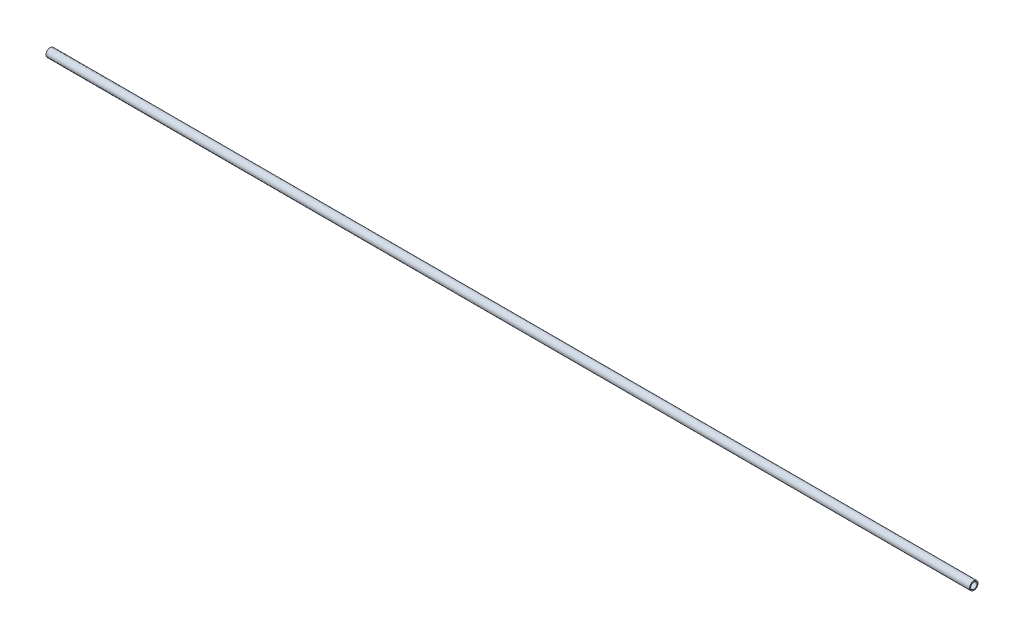
SolidWorks part; units mm, degrees
material "AISI 4130 Steel, annealed at 865C"
ref_plane "Front Plane" through (0, 0, 0) normal (0, 0, 1) x (1, 0, 0)
ref_plane "Top Plane" through (0, 0, 0) normal (0, 1, 0) x (1, 0, 0)
ref_plane "Right Plane" through (0, 0, 0) normal (1, 0, 0) x (0, 0, -1)
sketch "Sketch1" plane through (0, 0, 0) normal (1, 0, 0) x (0, 0, -1)
  circle A0 centre (0, 0) radius 12.7
  circle A1 centre (0, 0) radius 9.652
  dimension "D1" = 25.4
  dimension "D2" = 19.304
extrude "Boss-Extrude1" add sketch "Sketch1" along normal blind 2800
